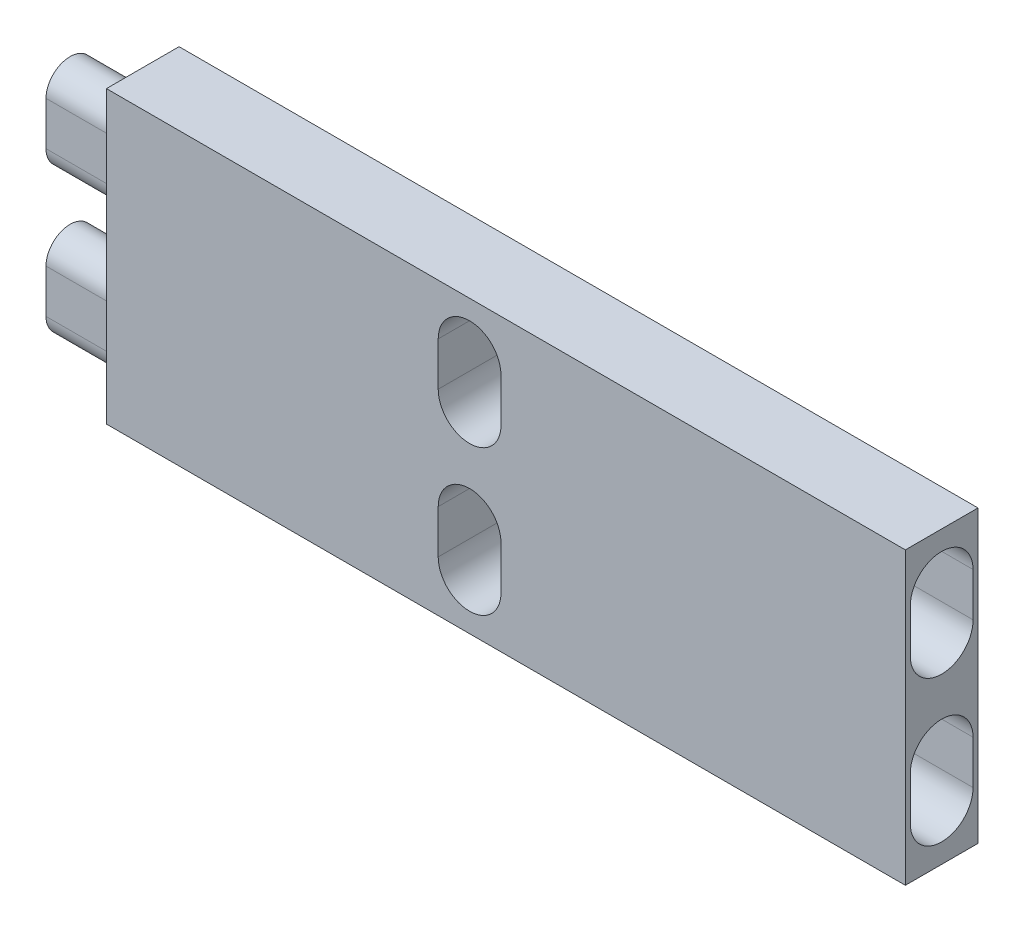
SolidWorks part; units mm, degrees
ref_plane "Front Plane" through (0, 0, 0) normal (0, 0, 1) x (1, 0, 0)
ref_plane "Top Plane" through (0, 0, 0) normal (0, 1, 0) x (1, 0, 0)
ref_plane "Right Plane" through (0, 0, 0) normal (1, 0, 0) x (0, 0, -1)
sketch "Sketch1" plane through (0, 0, 0) normal (0, 0, 1) x (1, 0, 0)
  line L1 (30, -10) -> (-30, -10)
  line L2 (30, -10) -> (30, 10)
  line L3 (30, 10) -> (-30, 10)
  line L4 (-30, -10) -> (-30, 10)
  line L5 (30, -10) -> (-30, 10) construction
  line L6 (30, 10) -> (-30, -10) construction
  point P0 (0, 0)
  dimension "D1" = 20
  dimension "D2" = 60
extrude "Boss-Extrude1" add sketch "Sketch1" along normal mid plane 5
sketch "Sketch2" plane through (-30, 0, 0) normal (-1, 0, 0) x (0, 0, 1)
  line L0 (0, 6.5) -> (0, 3.5) construction
  line L1 (1.66, 6.5) -> (1.66, 3.5)
  line L2 (-1.66, 6.5) -> (-1.66, 3.5)
  line L3 (0, -3.5) -> (0, -6.5) construction
  line L4 (1.66, -3.5) -> (1.66, -6.5)
  line L5 (-1.66, -3.5) -> (-1.66, -6.5)
  line L6 (0, 5) -> (0, -5) construction
  line L8 (-2.5, 10) -> (2.5, 10)
  line L9 (-2.5, 10) -> (-2.5, -10)
  line L10 (-2.5, -10) -> (2.5, -10)
  line L11 (2.5, 10) -> (2.5, -10)
  arc A0 (1.66, 6.5) -> (-1.66, 6.5) centre (0, 6.5) ccw
  arc A1 (-1.66, 3.5) -> (1.66, 3.5) centre (0, 3.5) ccw
  arc A2 (1.66, -3.5) -> (-1.66, -3.5) centre (0, -3.5) ccw
  arc A3 (-1.66, -6.5) -> (1.66, -6.5) centre (0, -6.5) ccw
  point P3 (0, 5)
  point P8 (0, -5)
  point P17 (0, 0)
  point P18 (0, 0)
  dimension "D1" = 1.66
  dimension "D2" = 3
  dimension "D3" = 10
extrude "Cut-Extrude1" cut sketch "Sketch2" against normal blind 5
sketch "Sketch3" plane through (30, 0, 0) normal (1, 0, 0) x (0, 0, -1)
  line L102 (2.16, 3.5) -> (2.16, 6.5)
  line L103 (-2.16, 6.5) -> (-2.16, 3.5)
  line L104 (2.16, 3.5) -> (2.16, 6.5)
  line L105 (-2.16, 6.5) -> (-2.16, 3.5)
  line L111 (2.16, -6.5) -> (2.16, -3.5)
  line L112 (-2.16, -3.5) -> (-2.16, -6.5)
  line L113 (2.16, -6.5) -> (2.16, -3.5)
  line L114 (-2.16, -3.5) -> (-2.16, -6.5)
  arc A105 (-2.16, 3.5) -> (2.16, 3.5) centre (0, 3.5) ccw
  arc A106 (2.16, 6.5) -> (-2.16, 6.5) centre (0, 6.5) ccw
  arc A107 (-2.16, 3.5) -> (2.16, 3.5) centre (0, 3.5) ccw
  arc A108 (2.16, 6.5) -> (-2.16, 6.5) centre (0, 6.5) ccw
  arc A114 (-2.16, -6.5) -> (2.16, -6.5) centre (0, -6.5) ccw
  arc A115 (2.16, -3.5) -> (-2.16, -3.5) centre (0, -3.5) ccw
  arc A116 (-2.16, -6.5) -> (2.16, -6.5) centre (0, -6.5) ccw
  arc A117 (2.16, -3.5) -> (-2.16, -3.5) centre (0, -3.5) ccw
  dimension "D1" = 0.5
  dimension "D2" = 0.5
extrude "Cut-Extrude2" cut sketch "Sketch3" against normal blind 6
sketch "Sketch4" plane through (0, 0, -2.5) normal (0, 0, -1) x (-1, 0, 0)
  line L0 (0, 0) -> (0, 5) construction
  line L1 (0, 6.5) -> (0, 3.5) construction
  line L2 (2.16, 6.5) -> (2.16, 3.5)
  line L3 (-2.16, 6.5) -> (-2.16, 3.5)
  line L7 (0, -6.5) -> (0, -3.5) construction
  line L8 (-2.16, -6.5) -> (-2.16, -3.5)
  line L9 (2.16, -6.5) -> (2.16, -3.5)
  line L10 (0, 0) -> (0, -5) construction
  arc A0 (2.16, 6.5) -> (-2.16, 6.5) centre (0, 6.5) ccw
  arc A1 (-2.16, 3.5) -> (2.16, 3.5) centre (0, 3.5) ccw
  arc A2 (-2.16, -6.5) -> (2.16, -6.5) centre (0, -6.5) ccw
  arc A3 (2.16, -3.5) -> (-2.16, -3.5) centre (0, -3.5) ccw
  point P5 (0, 5)
  point P12 (0, -5)
  dimension "D1" = 2.16
  dimension "D2" = 3
  dimension "D3" = 13
extrude "Cut-Extrude3" cut sketch "Sketch4" against normal blind 6
